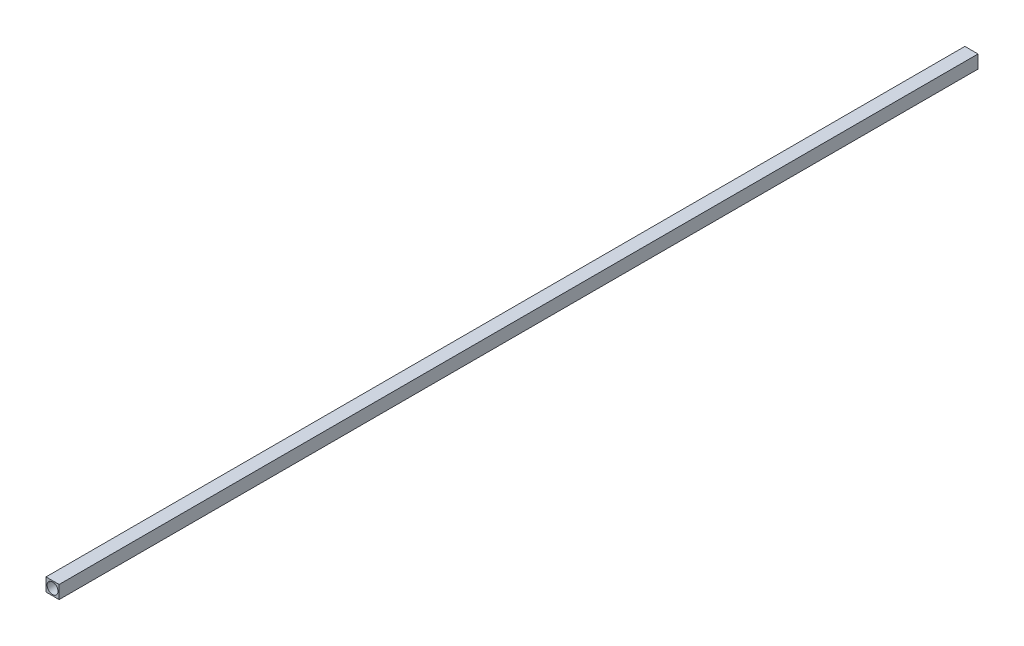
SolidWorks part; units mm, degrees
ref_plane "Front Plane" through (0, 0, 0) normal (0, 0, 1) x (1, 0, 0)
ref_plane "Top Plane" through (0, 0, 0) normal (0, 1, 0) x (1, 0, 0)
ref_plane "Right Plane" through (0, 0, 0) normal (1, 0, 0) x (0, 0, -1)
sketch "Sketch1" plane through (0, 0, 0) normal (0, 0, 1) x (1, 0, 0)
  line L0 (3, 6) -> (3, 0) construction
  line L1 (0, 0) -> (6, 0)
  line L2 (0, 0) -> (0, 6)
  line L3 (0, 6) -> (6, 6)
  line L4 (6, 0) -> (6, 6)
  line L5 (0, 3) -> (6, 3) construction
  circle A0 centre (3, 3) radius 2.5
  dimension "D3" = 5
  dimension "D1" = 6
  dimension "D2" = 6
extrude "Boss-Extrude1" add sketch "Sketch1" along normal blind 420
